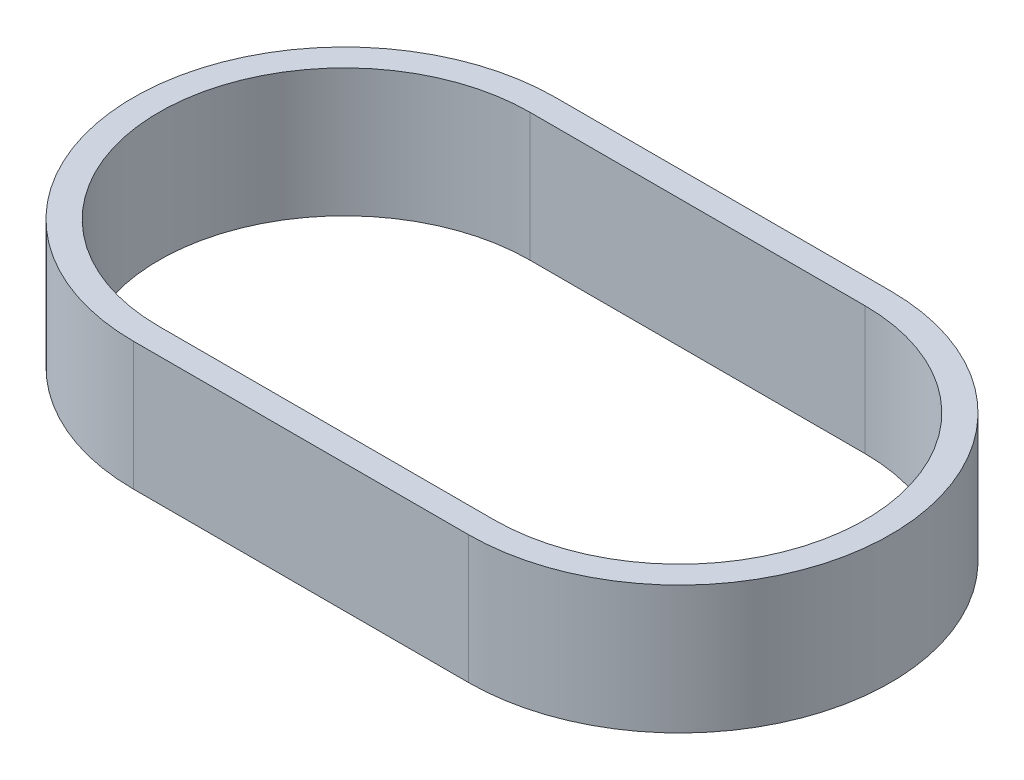
SolidWorks part; units mm, degrees
ref_plane "Front Plane" through (0, 0, 0) normal (0, 0, 1) x (1, 0, 0)
ref_plane "Top Plane" through (0, 0, 0) normal (0, 1, 0) x (1, 0, 0)
ref_plane "Right Plane" through (0, 0, 0) normal (1, 0, 0) x (0, 0, -1)
sketch "Sketch1" plane through (0, 0, 0) normal (0, 1, 0) x (1, 0, 0)
  line L0 (-13.081, 0) -> (13.081, 0) construction
  line L1 (-13.081, 14.478) -> (13.081, 14.478)
  line L2 (-13.081, -14.478) -> (13.081, -14.478)
  line L3 (-13.081, 16.478) -> (13.081, 16.478)
  line L4 (-13.081, -16.478) -> (13.081, -16.478)
  arc A0 (-13.081, 14.478) -> (-13.081, -14.478) centre (-13.081, 0) ccw
  arc A1 (13.081, -14.478) -> (13.081, 14.478) centre (13.081, 0) ccw
  arc A2 (13.081, -16.478) -> (13.081, 16.478) centre (13.081, 0) ccw
  arc A3 (-13.081, 16.478) -> (-13.081, -16.478) centre (-13.081, 0) ccw
  point P2 (0, 0)
  dimension "D2" = 26.162
  dimension "D1" = 28.956
  dimension "D3" = 2
extrude "Boss-Extrude1" add sketch "Sketch1" along normal blind 10 contours A3 L4 A2 L3 | L2 A1 L1 A0
